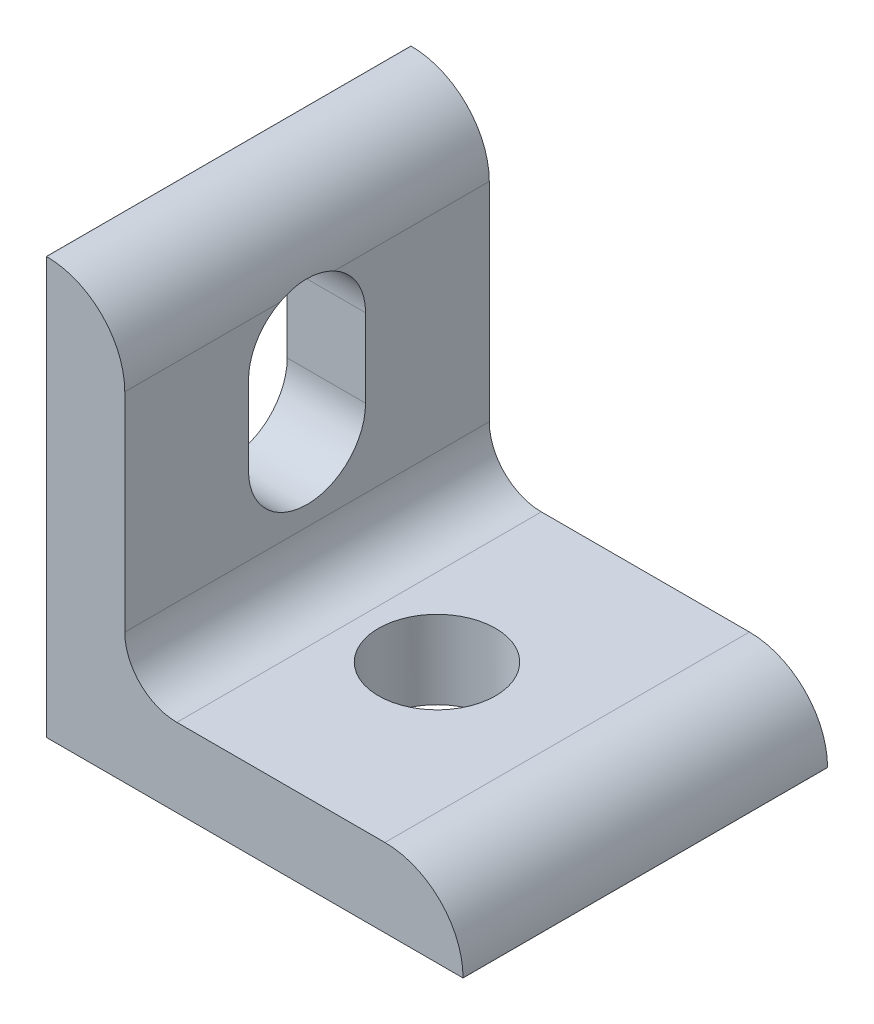
SolidWorks part; units mm, degrees
material "6105-T5 Aluminum"
ref_plane "Front Plane" through (0, 0, 0) normal (0, 0, 1) x (1, 0, 0)
ref_plane "Top Plane" through (0, 0, 0) normal (0, 1, 0) x (1, 0, 0)
ref_plane "Right Plane" through (0, 0, 0) normal (1, 0, 0) x (0, 0, -1)
sketch "Sketch2" plane through (0, 0, 0) normal (0, 0, 1) x (1, 0, 0)
  line L0 (0, 0) -> (0, 25.4)
  line L1 (25.4, 0.0127) -> (25.4, 0)
  line L2 (4.7752, 20.6375) -> (4.7752, 7.9502)
  line L3 (7.9502, 4.7752) -> (20.6375, 4.7752)
  line L4 (0, 25.4) -> (0.0127, 25.4)
  line L5 (25.4, 0) -> (0, 0)
  arc A0 (20.6375, 4.7752) -> (25.4, 0.0127) centre (20.6375, 0.0127) cw
  arc A1 (4.7752, 20.6375) -> (0.0127, 25.4) centre (0.0127, 20.6375) ccw
  arc A2 (4.7752, 7.9502) -> (7.9502, 4.7752) centre (7.9502, 7.9502) ccw
  dimension "D3" = 25.4
  dimension "D4" = 3.175
  dimension "D6" = 4.7625
  dimension "D1" = 4.7752
  dimension "D2" = 4.7752
  dimension "D5" = 25.4
extrude "Boss-Extrude1" add sketch "Sketch2" along normal mid plane 22.225
sketch "Sketch3" plane through (0, 0, 0) normal (-1, 0, 0) x (0, 0, 1)
  line L0 (11.1125, 0) -> (-11.1125, 0) construction
  line L1 (-3.5687, 17.4752) -> (-3.5687, 12.7)
  line L2 (3.5687, 17.4752) -> (3.5687, 12.7)
  line L3 (0, 12.7) -> (0, 0) construction
  arc A0 (3.5687, 17.4752) -> (-3.5687, 17.4752) centre (0, 17.4752) ccw
  arc A1 (-3.5687, 12.7) -> (3.5687, 12.7) centre (0, 12.7) ccw
  dimension "D3" = 12.7
  dimension "D1" = 7.1374
  dimension "D2" = 4.7752
extrude "Cut-Extrude1" cut sketch "Sketch3" against normal up to next
sketch "Sketch4" plane through (0, 0, 0) normal (0, -1, 0) x (1, 0, 0)
  line L0 (0, 11.1125) -> (0, -11.1125) construction
  line L2 (0, 0) -> (12.7, 0) construction
  circle A0 centre (12.7, 0) radius 3.5687
  dimension "D1" = 7.1374
  dimension "D2" = 12.7
extrude "Cut-Extrude2" cut sketch "Sketch4" against normal through all
